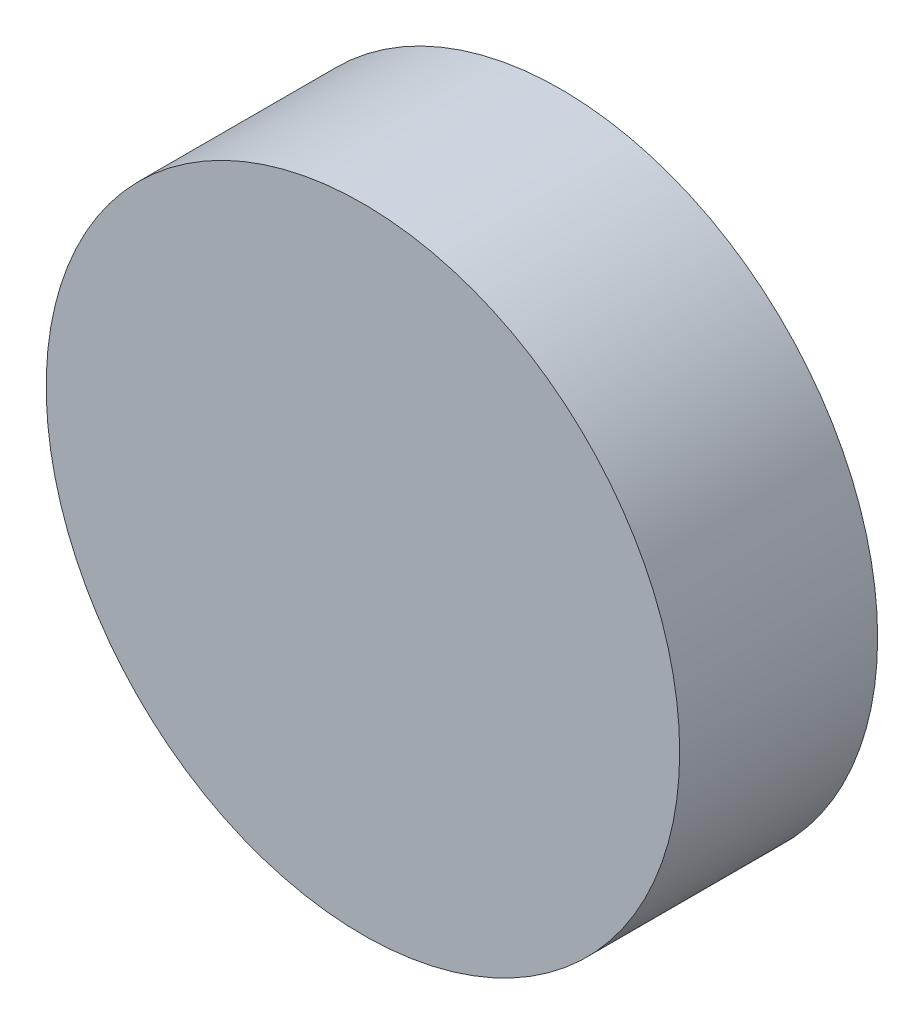
SolidWorks part; units mm, degrees
ref_plane "前视基准面" through (0, 0, 0) normal (0, 0, 1) x (1, 0, 0)
ref_plane "上视基准面" through (0, 0, 0) normal (0, 1, 0) x (1, 0, 0)
ref_plane "右视基准面" through (0, 0, 0) normal (1, 0, 0) x (0, 0, -1)
other "Configuration Table"
sketch "草图1" plane through (0, 0, 0) normal (0, 0, 1) x (1, 0, 0)
  circle A0 centre (0, 0) radius 8
  dimension "diameter" = 16
extrude "Pitch_Motor" add sketch "草图1" along normal blind 5
